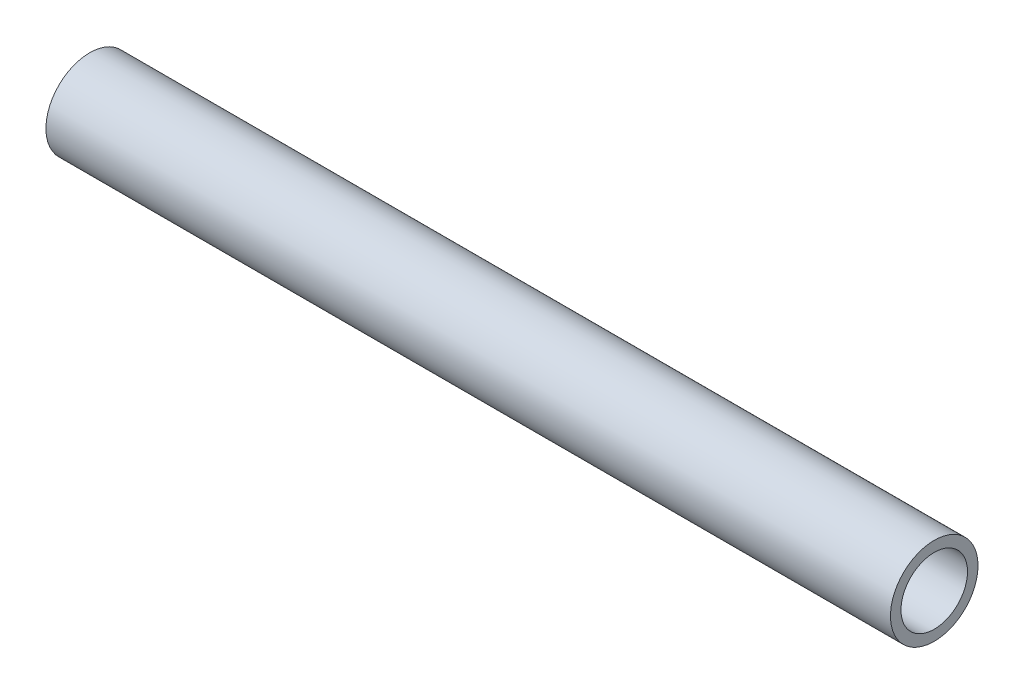
SolidWorks part; units mm, degrees
material "AISI 4130 Steel, annealed at 865C"
ref_plane "Front Plane" through (0, 0, 0) normal (0, 0, 1) x (1, 0, 0)
ref_plane "Top Plane" through (0, 0, 0) normal (0, 1, 0) x (1, 0, 0)
ref_plane "Right Plane" through (0, 0, 0) normal (1, 0, 0) x (0, 0, -1)
sketch "Sketch1" plane through (0, 0, 0) normal (1, 0, 0) x (0, 0, -1)
  circle A0 centre (0, 0) radius 12.7
  circle A1 centre (0, 0) radius 9.652
  dimension "D1" = 25.4
  dimension "D2" = 19.304
extrude "Boss-Extrude1" add sketch "Sketch1" along normal blind 245
